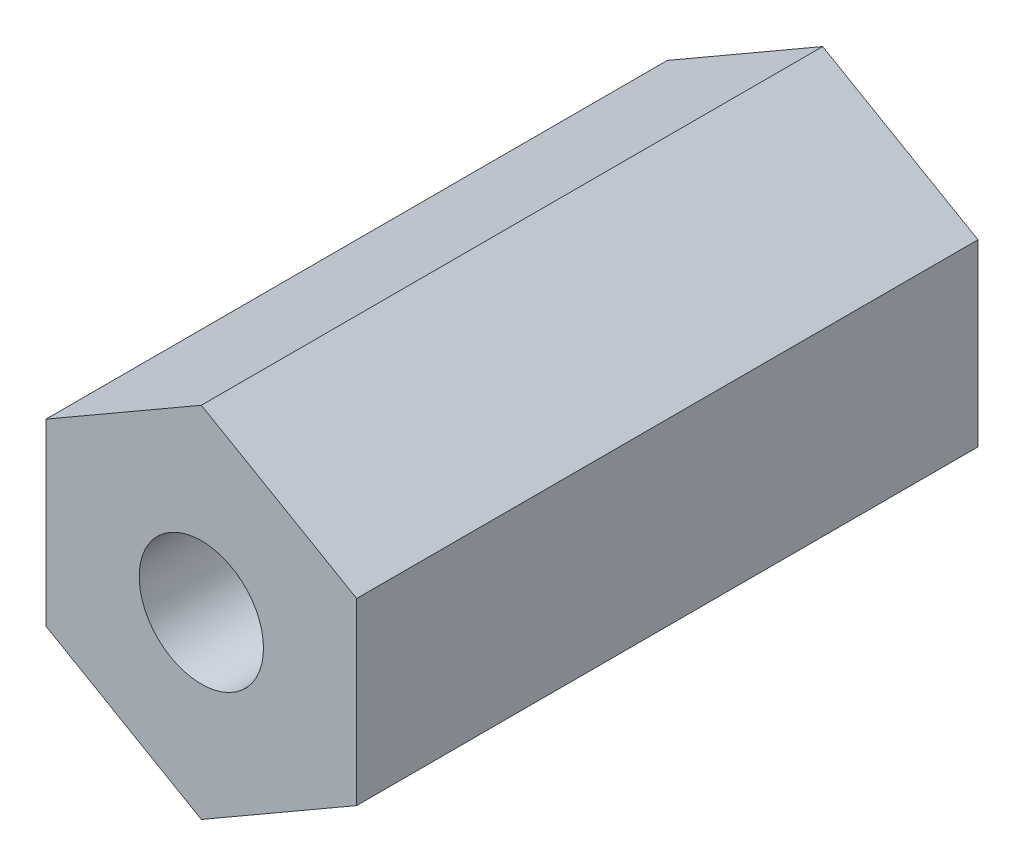
SolidWorks part; units mm, degrees
ref_plane "Front Plane" through (0, 0, 0) normal (0, 0, 1) x (1, 0, 0)
ref_plane "Top Plane" through (0, 0, 0) normal (0, 1, 0) x (1, 0, 0)
ref_plane "Right Plane" through (0, 0, 0) normal (1, 0, 0) x (0, 0, -1)
sketch "Sketch1" plane through (0, 0, 0) normal (0, 0, 1) x (1, 0, 0)
  line L1 (6.35, 3.6662) -> (0, 7.3323)
  line L2 (0, 7.3323) -> (-6.35, 3.6662)
  line L3 (-6.35, 3.6662) -> (-6.35, -3.6662)
  line L4 (-6.35, -3.6662) -> (0, -7.3323)
  line L5 (0, -7.3323) -> (6.35, -3.6662)
  line L6 (6.35, -3.6662) -> (6.35, 3.6662)
  circle A0 centre (0, 0) radius 6.35 construction
  dimension "D1" = 12.7
extrude "Boss-Extrude1" add sketch "Sketch1" along normal mid plane 25.4 contours L2 L3 L4 L5 L6 L1
sketch "Sketch2" plane through (0, 0, 12.7) normal (0, 0, 1) x (1, 0, 0)
  circle A0 centre (0, 0) radius 2.54
  dimension "D1" = 5.08
extrude "Cut-Extrude1" cut sketch "Sketch2" against normal through all both and the other way through all
